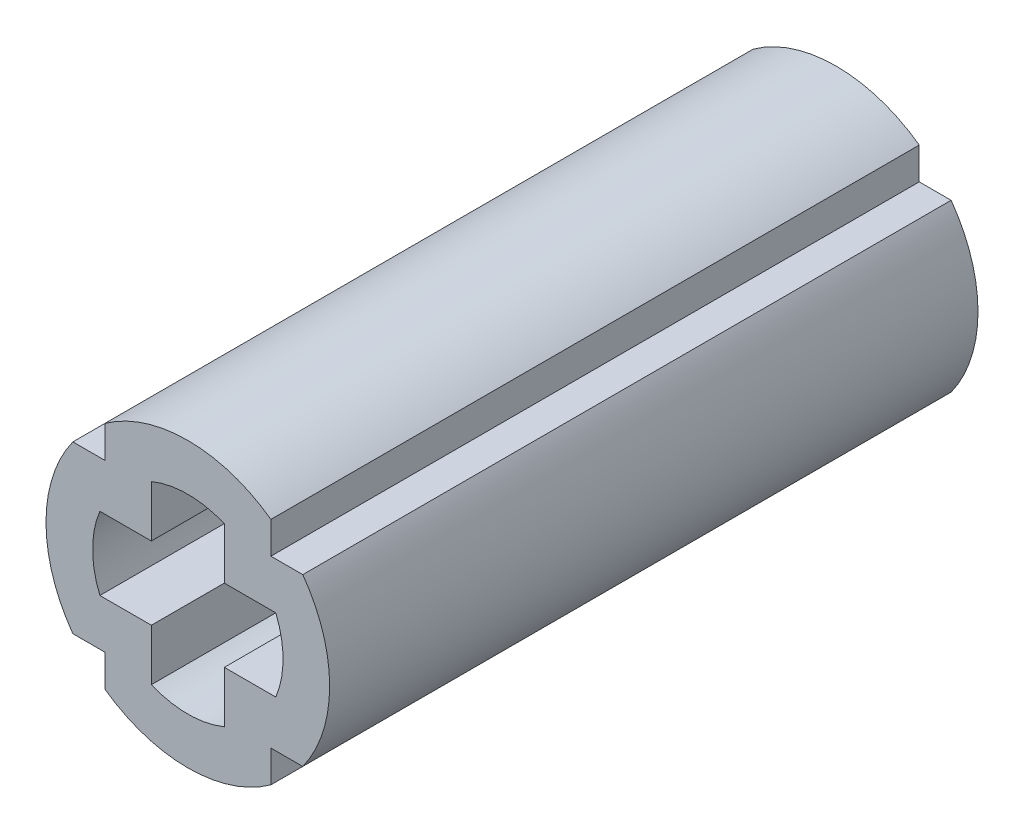
SolidWorks part; units mm, degrees
ref_plane "Front Plane" through (0, 0, 0) normal (0, 0, 1) x (1, 0, 0)
ref_plane "Top Plane" through (0, 0, 0) normal (0, 1, 0) x (1, 0, 0)
ref_plane "Right Plane" through (0, 0, 0) normal (1, 0, 0) x (0, 0, -1)
sketch "Sketch1" plane through (0, 0, 0) normal (0, 0, 1) x (1, 0, 0)
  line L0 (-0.9, 2.1708) -> (-0.9, 0.9)
  line L1 (0.9, 2.1708) -> (0.9, 0.9)
  line L2 (-2.1708, 0.9) -> (-0.9, 0.9)
  line L3 (-2.1708, -0.9) -> (-0.9, -0.9)
  line L4 (0.9, 0.9) -> (2.1708, 0.9)
  line L5 (-0.9, -0.9) -> (-0.9, -2.1708)
  line L6 (0.9, -0.9) -> (2.1708, -0.9)
  line L7 (0.9, -0.9) -> (0.9, -2.1708)
  line L8 (-2.05, 2.8368) -> (-2.05, 2.05)
  line L9 (-2.8368, 2.05) -> (-2.05, 2.05)
  line L10 (-2.8368, -2.05) -> (-2.05, -2.05)
  line L11 (-2.05, -2.05) -> (-2.05, -2.8368)
  line L12 (2.05, -2.05) -> (2.05, -2.8368)
  line L13 (2.05, -2.05) -> (2.8368, -2.05)
  line L14 (2.05, 2.05) -> (2.8368, 2.05)
  line L15 (2.05, 2.8368) -> (2.05, 2.05)
  arc A0 (-2.1708, 0.9) -> (-2.1708, -0.9) centre (0, 0) ccw
  arc A1 (0.9, 2.1708) -> (-0.9, 2.1708) centre (0, 0) ccw
  arc A2 (2.1708, -0.9) -> (2.1708, 0.9) centre (0, 0) ccw
  arc A3 (-0.9, -2.1708) -> (0.9, -2.1708) centre (0, 0) ccw
  arc A4 (-2.8368, 2.05) -> (-2.8368, -2.05) centre (0, 0) ccw
  arc A5 (-2.05, -2.8368) -> (2.05, -2.8368) centre (0, 0) ccw
  arc A6 (2.8368, -2.05) -> (2.8368, 2.05) centre (0, 0) ccw
  arc A7 (2.05, 2.8368) -> (-2.05, 2.8368) centre (0, 0) ccw
  dimension "D1" = 4.7
  dimension "D2" = 0.9
  dimension "D3" = 0.9
  dimension "D4" = 0.9
  dimension "D5" = 0.9
  dimension "D6" = 1.15
extrude "Boss-Extrude1" add sketch "Sketch1" along normal blind 16
